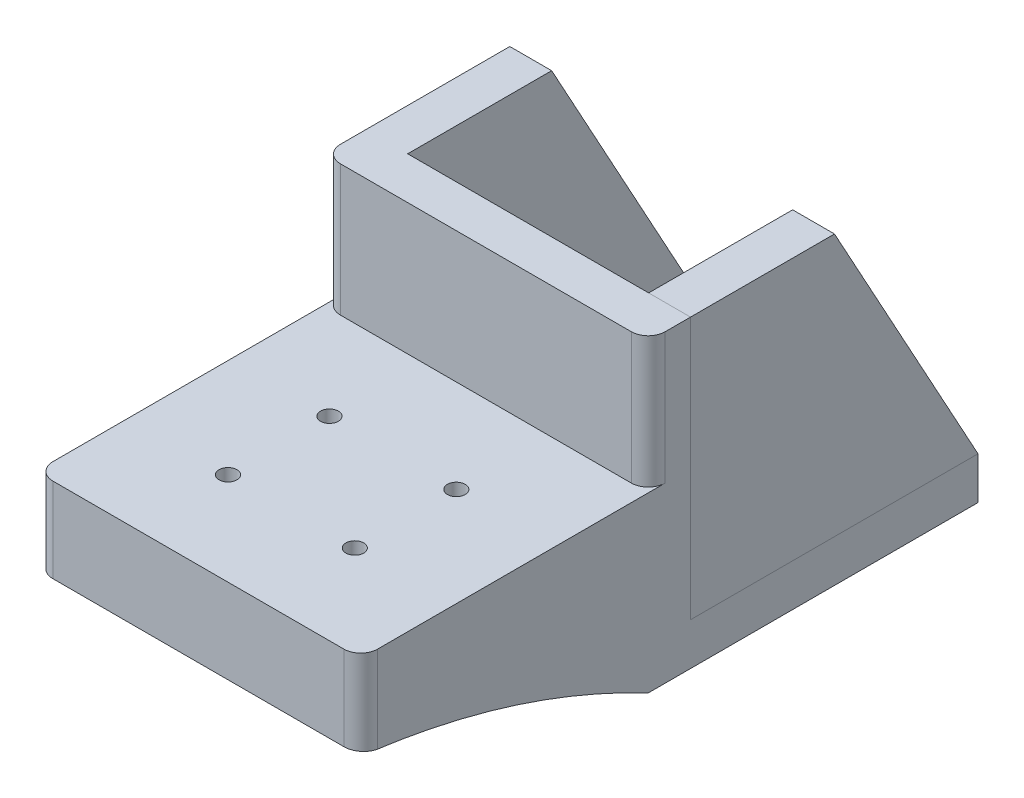
SolidWorks part; units mm, degrees
ref_plane "Front Plane" through (0, 0, 0) normal (0, 0, 1) x (1, 0, 0)
ref_plane "Top Plane" through (0, 0, 0) normal (0, 1, 0) x (1, 0, 0)
ref_plane "Right Plane" through (0, 0, 0) normal (1, 0, 0) x (0, 0, -1)
sketch "Sketch1" plane through (0, 0, 0) normal (0, 1, 0) x (1, 0, 0)
  circle A0 centre (0, 0) radius 9.6
  dimension "D1" = 19.2
extrude "Boss-Extrude1" add sketch "Sketch1" along normal blind 15.7
sketch "Sketch3" plane through (0, 15.7, 0) normal (0, 1, 0) x (1, 0, 0)
  line L1 (-14.25, -17) -> (14.25, -17) construction
  line L2 (-14.25, -17) -> (-14.25, 17) construction
  line L3 (-14.25, 17) -> (14.25, 17) construction
  line L4 (14.25, -17) -> (14.25, 17) construction
  line L5 (-14.25, -17) -> (14.25, 17) construction
  line L6 (-14.25, 17) -> (14.25, -17) construction
  line L7 (-19.2, -17) -> (19.2, -17)
  line L8 (-19.2, -17) -> (-19.2, 17)
  line L9 (-19.2, 17) -> (19.2, 17)
  line L10 (19.2, -17) -> (19.2, 17)
  line L11 (-19.2, -17) -> (19.2, 17) construction
  line L12 (-19.2, 17) -> (19.2, -17) construction
  point P1 (0, 0)
  point P7 (0, 0)
  dimension "D1" = 34
  dimension "D2" = 28.5
  dimension "D3" = 0
  dimension "D4" = 4.95
extrude "Boss-Extrude2" add sketch "Sketch3" along normal blind 5
sketch "Sketch2" plane through (0, 0, 0) normal (0, -1, 0) x (-1, 0, 0)
  circle A0 centre (0, 0) radius 6 construction
  circle A1 centre (0, -6) radius 1.1
  circle A2 centre (0, 6) radius 1.1
  circle A3 centre (-6, 0) radius 1.1
  circle A4 centre (6, 0) radius 1.1
  dimension "D1" = 12
  dimension "D2" = 2.2
  dimension "D3" = 2.2
  dimension "D4" = 2.2
  dimension "D5" = 2.2
extrude "Cut-Extrude1" cut sketch "Sketch2" against normal through all
sketch "Sketch7" plane through (0, 15.7, 0) normal (0, -1, 0) x (1, 0, 0)
  line L1 (-19.2, 17) -> (19.2, 17)
  line L2 (-19.2, 17) -> (-19.2, 56)
  line L3 (-19.2, 56) -> (19.2, 56)
  line L4 (19.2, 17) -> (19.2, 56)
  dimension "D1" = 39
extrude "Boss-Extrude3" add sketch "Sketch7" against normal blind 20.5
sketch "Sketch11" plane through (0, 36.2, 0) normal (0, 1, 0) x (1, 0, 0)
  line L0 (19.2, -17) -> (19.2, -56) construction
  line L1 (-19.2, -17) -> (19.2, -17)
  line L2 (-19.2, -17) -> (-19.2, -22)
  line L3 (-19.2, -22) -> (19.2, -22)
  line L4 (19.2, -17) -> (19.2, -22)
  dimension "D1" = 5
extrude "Boss-Extrude7" add sketch "Sketch11" along normal blind 46.6
sketch "Sketch12" plane through (19.2, 0, 0) normal (1, 0, 0) x (0, 0, -1)
  line L0 (-17, 82.8) -> (-17, 20.7)
  line L1 (-17, 20.7) -> (17, 20.7)
  line L2 (17, 20.7) -> (-17, 82.8)
extrude "Boss-Extrude8" add sketch "Sketch12" against normal blind 4.95 separate body
sketch "Sketch13" plane through (-19.2, 0, 0) normal (-1, 0, 0) x (0, 0, 1)
  line L0 (17, 82.8) -> (17, 20.7)
  line L1 (17, 20.7) -> (-17, 20.7)
  line L2 (-17, 20.7) -> (17, 82.8)
extrude "Boss-Extrude9" add sketch "Sketch13" against normal blind 4.95
fillet "Fillet2" radius 2 2 edges at (-19.2, 25.95, 56) (19.2, 25.95, 56)
sketch "Sketch14" plane through (0, 36.2, 0) normal (0, 1, 0) x (1, 0, 0)
  line L0 (-19.2, -22) -> (19.2, -22) construction
  line L1 (-14.25, -22) -> (14.25, -22)
  line L2 (-14.25, -22) -> (-14.25, -56)
  line L3 (-14.25, -56) -> (14.25, -56)
  line L4 (14.25, -22) -> (14.25, -56)
  line L5 (17.2, -56) -> (-17.2, -56) construction
  line L6 (-19.2, -22) -> (19.2, -22) construction
  point P10 (0, -22)
  point P11 (0, -22)
  dimension "D1" = 28.5
sketch "Sketch15" plane through (19.2, 0, 0) normal (1, 0, 0) x (0, 0, -1)
  line L0 (-56, 15.7) -> (-56, 36.2) construction
  line L1 (-54, 15.7) -> (17, 15.7) construction
  line L3 (-54, 36.2) -> (-54, 15.7) construction
  line L4 (-22, 36.2) -> (-56, 36.2) construction
  line L5 (-22, 36.2) -> (-56, 36.2) construction
  line L6 (-56, 26.2) -> (-56, 15.7)
  line L7 (-56, 15.7) -> (-22, 15.7)
  spline S0 degree 2 poles (-56, 26.2) (-38.0648, 24.1612) (-22, 15.7) knots 0 0 0 1 1 1
  dimension "D1" = 10
  dimension "D2" = 12.5339
  dimension "D3" = 12.79
extrude "Cut-Extrude5" cut sketch "Sketch15" against normal through all
sketch "Sketch16" plane through (0, 0, 22) normal (0, 0, 1) x (1, 0, 0)
  line L0 (19.2, 82.8) -> (19.2, 36.2) construction
  line L1 (-14.25, 65.5) -> (-7.25, 65.5)
  line L2 (-14.25, 65.5) -> (-14.25, 51.7)
  line L3 (-14.25, 51.7) -> (-7.25, 51.7)
  line L4 (-7.25, 65.5) -> (-7.25, 51.7)
  line L5 (14.25, 65.5) -> (7.25, 65.5)
  line L6 (14.25, 65.5) -> (14.25, 51.7)
  line L7 (14.25, 51.7) -> (7.25, 51.7)
  line L8 (7.25, 65.5) -> (7.25, 51.7)
  line L9 (-14.25, 36.2) -> (14.25, 36.2) construction
  line L10 (-19.2, 82.8) -> (-19.2, 36.2) construction
  dimension "D1" = 13.8
  dimension "D2" = 13.8
  dimension "D3" = 4.95
  dimension "D4" = 4.95
  dimension "D5" = 7
  dimension "D6" = 7
  dimension "D7" = 15.5
  dimension "D8" = 15.5
extrude "Cut-Extrude9" cut sketch "Sketch16" against normal through all
sketch "Sketch18" plane through (0, 36.2, 0) normal (0, 1, 0) x (1, 0, 0)
  line L0 (-7.5, -33) -> (7.5, -33) construction
  line L1 (-12.2951, -22) -> (-12.2951, -56) construction
  line L2 (17.2, -56) -> (-17.2, -56) construction
  line L3 (-7.5, -33) -> (-7.5, -45) construction
  line L5 (-19.2, -22) -> (19.2, -22) construction
  circle A0 centre (-7.5, -33) radius 1.05
  circle A1 centre (-7.5, -45) radius 1.05
  circle A2 centre (7.5, -33) radius 1.05
  circle A3 centre (7.5, -45) radius 1.05
  point P8 (0, -56)
  point P9 (0, -33)
  point P10 (-12.2951, -39)
  point P13 (-7.5, -39)
  dimension "D1" = 2.1
  dimension "D2" = 2.1
  dimension "D4" = 2.1
  dimension "D6" = 2.1
  dimension "D3" = 15
  dimension "D5" = 12
extrude "Cut-Extrude10" cut sketch "Sketch18" against normal through all
ref_plane "Plane1" through (0, 5.7, 0) normal (0, -1, 0) x (-1, 0, 0)
sketch "Sketch19" plane through (0, 5.7, 0) normal (0, -1, 0) x (-1, 0, 0)
  circle A0 centre (-7.5, -33) radius 2.5
  circle A1 centre (7.5, -33) radius 2.5
  circle A2 centre (-7.5, -45) radius 2.5
  circle A3 centre (7.5, -45) radius 2.5
  dimension "D1" = 5
  dimension "D2" = 5
  dimension "D3" = 5
  dimension "D4" = 5
extrude "Cut-Extrude11" cut sketch "Sketch19" against normal blind 27.5
sketch "Sketch20" plane through (19.2, 0, 0) normal (1, 0, 0) x (0, 0, -1)
  line L1 (-22, 15.7) -> (17, 15.7)
  line L2 (-22, 15.7) -> (-22, -2.1607)
  line L3 (-22, -2.1607) -> (17, -2.1607)
  line L4 (17, 15.7) -> (17, -2.1607)
  dimension "D1" = 17.8607
extrude "Cut-Extrude12" cut sketch "Sketch20" against normal through all
sketch "Sketch21" plane through (0, 15.7, 0) normal (0, -1, 0) x (1, 0, 0)
  circle A0 centre (0, 0) radius 8
  dimension "D1" = 16
extrude "Cut-Extrude13" cut sketch "Sketch21" against normal blind 3
fillet "Fillet3" radius 2 2 edges at (19.2, 59.5, 22) (-19.2, 59.5, 22)
sketch "Sketch22" plane through (0, 0, 22) normal (0, 0, 1) x (1, 0, 0)
  line L0 (19.2, 82.8) -> (19.2, 36.2) construction
  line L1 (-19.2, 82.8) -> (19.2, 82.8)
  line L2 (-19.2, 82.8) -> (-19.2, 51.7)
  line L3 (-19.2, 51.7) -> (19.2, 51.7)
  line L4 (19.2, 82.8) -> (19.2, 51.7)
  line L5 (-14.25, 51.7) -> (-7.25, 51.7) construction
extrude "Cut-Extrude14" cut sketch "Sketch22" against normal through all
